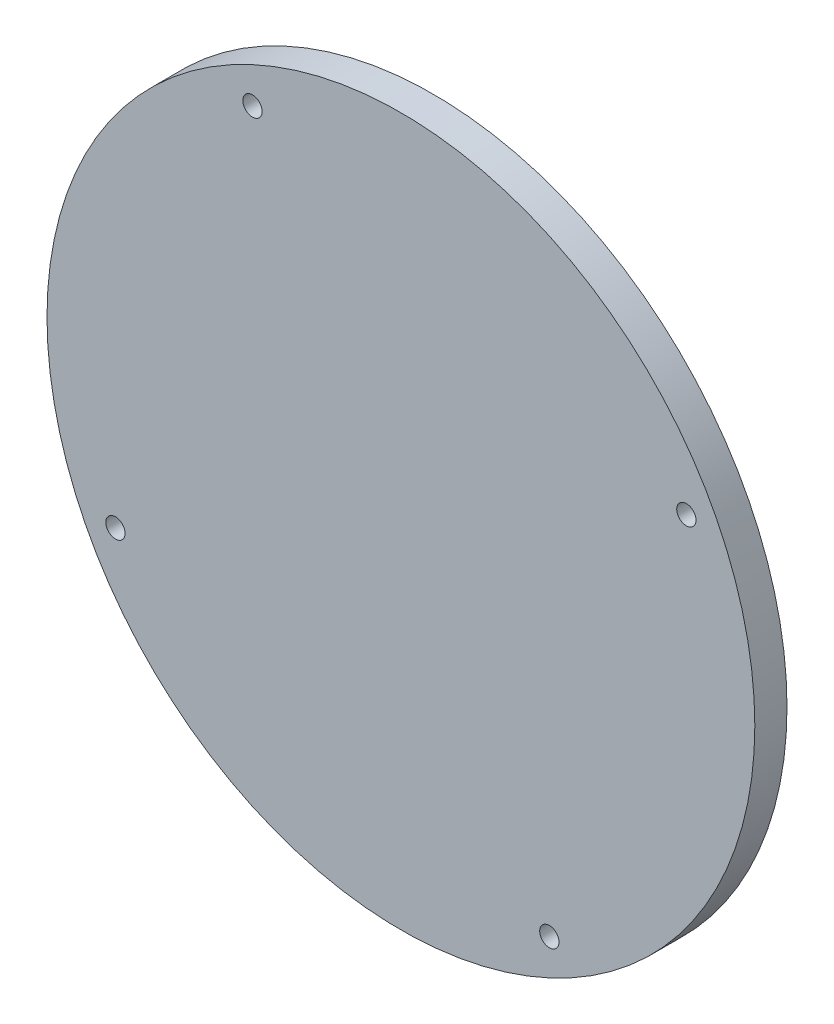
SolidWorks part; units mm, degrees
ref_plane "Plan de face" through (0, 0, 0) normal (0, 0, 1) x (1, 0, 0)
ref_plane "Plan de dessus" through (0, 0, 0) normal (0, 1, 0) x (1, 0, 0)
ref_plane "Plan de droite" through (0, 0, 0) normal (1, 0, 0) x (0, 0, -1)
sketch "Esquisse1" plane through (0, 0, 0) normal (0, 0, 1) x (1, 0, 0)
  circle A0 centre (0, 0) radius 55
  dimension "D1" = 110
extrude "Boss.-Extru.1" add sketch "Esquisse1" along normal blind 5
sketch "Esquisse2" plane through (0, 0, 5) normal (0, 0, 1) x (1, 0, 0)
  circle A0 centre (23.0682, -44.3605) radius 1.5
  circle A1 centre (-44.3605, -23.0682) radius 1.5
  circle A2 centre (-23.0682, 44.3605) radius 1.5
  circle A3 centre (44.3605, 23.0682) radius 1.5
extrude "Enlèv. mat.-Extru.1" cut sketch "Esquisse2" against normal through all
